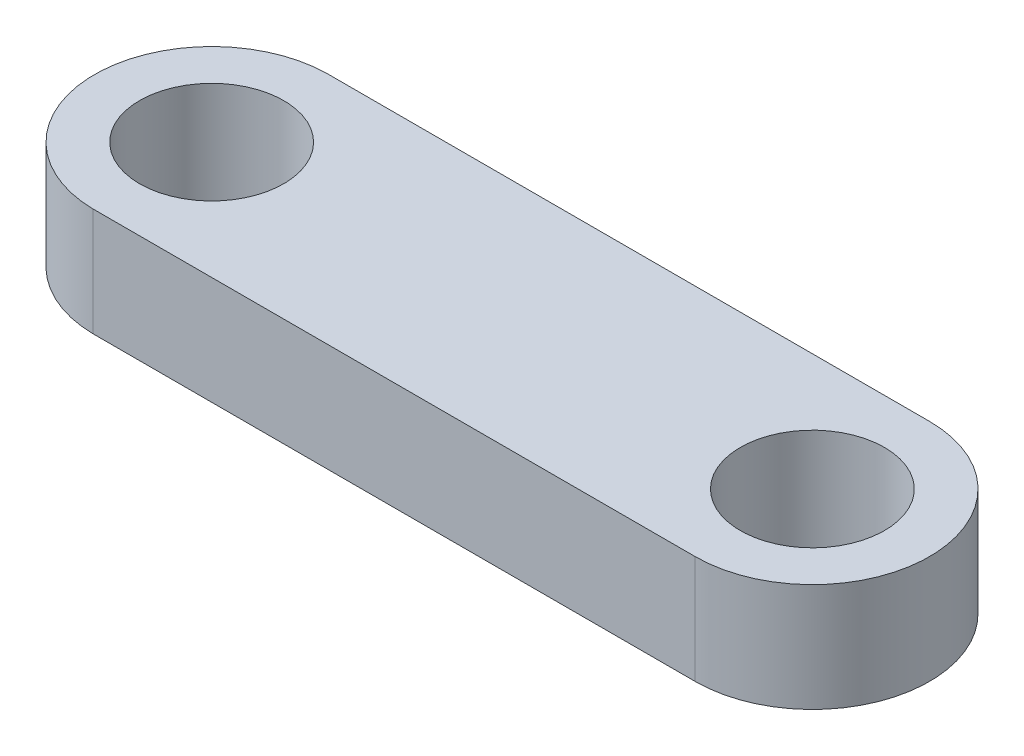
SolidWorks part; units mm, degrees
ref_plane "Plan de face" through (0, 0, 0) normal (0, 0, 1) x (1, 0, 0)
ref_plane "Plan de dessus" through (0, 0, 0) normal (0, 1, 0) x (1, 0, 0)
ref_plane "Plan de droite" through (0, 0, 0) normal (1, 0, 0) x (0, 0, -1)
sketch "Esquisse1" plane through (0, 0, 0) normal (0, 1, 0) x (1, 0, 0)
  line L1 (0, 0) -> (33.782, 0)
  line L3 (0, 6.604) -> (33.782, 6.604)
  arc A0 (0, 6.604) -> (0, 0) centre (0, 3.302) ccw
  arc A1 (33.782, 6.604) -> (33.782, 0) centre (33.782, 3.302) cw
  circle A2 centre (0, 3.302) radius 2.032
  circle A3 centre (33.782, 3.302) radius 2.032
  dimension "D3" = 4.064
  dimension "D4" = 4.064
  dimension "D1" = 33.782
  dimension "D2" = 6.604
extrude "Boss.-Extru.1" add sketch "Esquisse1" along normal blind 3.048
scale "Echelle1" scale about centroid uniform scaling yes scale factor 1.5
sketch "Esquisse2" plane through (0, 3.81, 0) normal (0, 1, 0) x (1, 0, 0)
  line L0 (-8.4455, 3.302) -> (42.2275, 3.302) construction
  circle A0 centre (16.8275, 3.302) radius 3.048
  point P2 (0, 0)
  dimension "D1" = 6.096
  dimension "D2" = 25.4
extrude "Enlèv. mat.-Extru.1" cut sketch "Esquisse2" against normal through all
sketch "Esquisse3" plane through (0, 3.81, 0) normal (0, 1, 0) x (1, 0, 0)
  line L0 (42.2275, 8.255) -> (-8.4455, 8.255) construction
  line L1 (-8.4455, -1.651) -> (42.2275, -1.651) construction
  line L2 (16.891, 8.255) -> (-13.3985, 8.255)
  line L3 (-13.3985, 8.255) -> (-13.3985, -1.651)
  line L4 (-13.3985, -1.651) -> (16.891, -1.651)
  arc A0 (16.891, 8.255) -> (16.891, -1.651) centre (16.8275, 3.302) ccw
  arc A3 (-8.4455, 8.255) -> (-8.4455, -1.651) centre (-8.4455, 3.302) ccw construction
  circle A6 centre (16.8275, 3.302) radius 3.048 construction
  circle M6 centre (-8.4455, 3.302) radius 3.048
  arc M7 (-8.4455, 8.255) -> (-8.4455, -1.651) centre (-8.4455, 3.302) ccw
  line M8 (-8.4455, -1.651) -> (42.2275, -1.651)
extrude "Enlèv. mat.-Extru.2" cut sketch "Esquisse3" against normal through all contours L2 L3 M7 | L3 L4 M7 | A0 L2 M7 M8 M6
